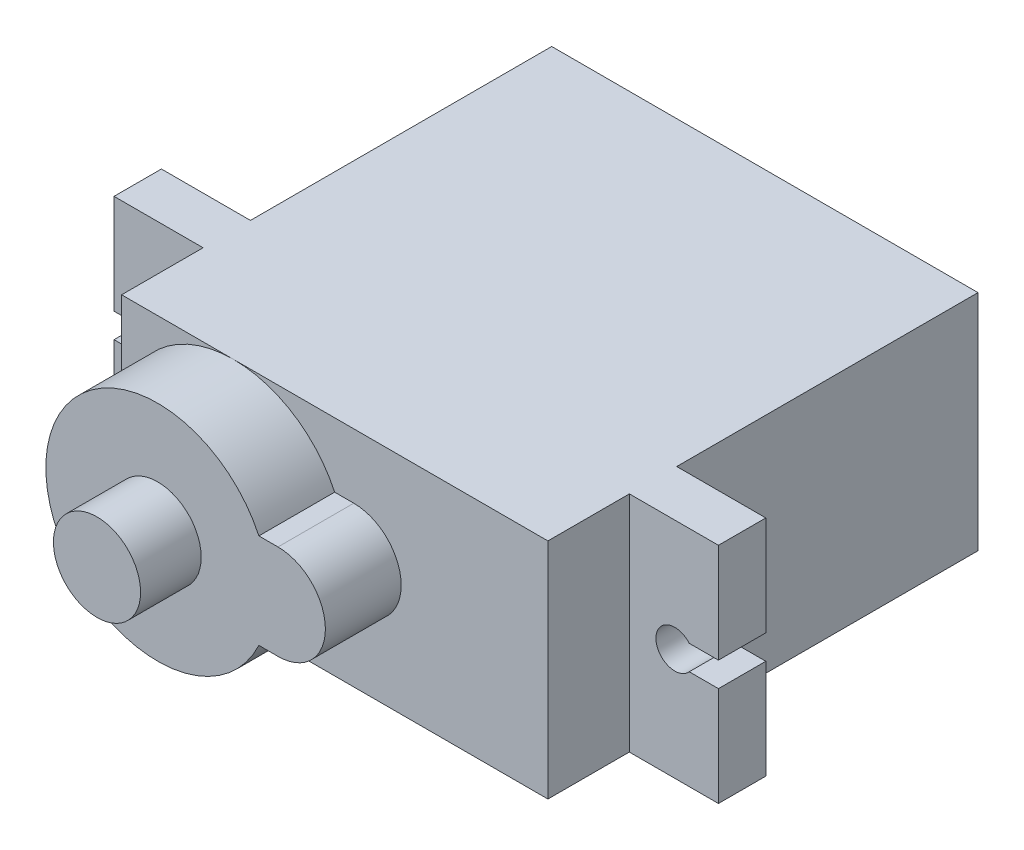
SolidWorks part; units mm, degrees
ref_plane "Alzado" through (0, 0, 0) normal (0, 0, 1) x (1, 0, 0)
ref_plane "Planta" through (0, 0, 0) normal (0, 1, 0) x (1, 0, 0)
ref_plane "Vista lateral" through (0, 0, 0) normal (1, 0, 0) x (0, 0, -1)
sketch "Croquis1" plane through (0, 0, 0) normal (0, 0, 1) x (1, 0, 0)
  line L1 (-11.25, -5.9) -> (11.25, -5.9)
  line L2 (-11.25, -5.9) -> (-11.25, 5.9)
  line L3 (-11.25, 5.9) -> (11.25, 5.9)
  line L4 (11.25, -5.9) -> (11.25, 5.9)
  line L5 (-11.25, -5.9) -> (11.25, 5.9) construction
  line L6 (-11.25, 5.9) -> (11.25, -5.9) construction
  point P0 (0, 0)
  dimension "D1" = 22.5
  dimension "D2" = 11.8
extrude "Saliente-Extruir1" add sketch "Croquis1" along normal blind 22.7
ref_plane "Soportes" through (0, 0, 15.9) normal (0, 0, 1) x (1, 0, 0)
sketch "Croquis2" plane through (0, 0, 15.9) normal (0, 0, 1) x (1, 0, 0)
  line L0 (-13.65, 0) -> (-15.95, -0.002) construction
  line L1 (11.25, 5.9) -> (15.95, 5.9)
  line L2 (11.25, 5.9) -> (11.25, -5.904)
  line L3 (11.25, -5.904) -> (15.95, -5.904)
  line L4 (15.95, 5.9) -> (15.95, 0.648)
  line L5 (-11.25, 5.9) -> (-15.95, 5.9)
  line L6 (-11.25, 5.9) -> (-11.25, -5.904)
  line L7 (-11.25, -5.904) -> (-15.95, -5.904)
  line L8 (-15.95, 5.9) -> (-15.95, 0.648)
  line L10 (-15.95, 0.648) -> (-14.4117, 0.648)
  line L11 (-15.95, -0.652) -> (-14.4082, -0.652)
  line L12 (-15.95, -0.652) -> (-15.95, -5.904)
  line L13 (15.95, 0.648) -> (14.4117, 0.648)
  line L14 (15.95, -0.652) -> (14.4082, -0.652)
  line L15 (15.95, -0.652) -> (15.95, -5.904)
  arc A0 (-14.4082, -0.652) -> (-14.4117, 0.648) centre (-13.65, 0) ccw
  arc A1 (14.4117, 0.648) -> (14.4082, -0.652) centre (13.65, 0) ccw
  point P17 (-15.95, 0.323)
  point P22 (15.95, -0.002)
  dimension "D2" = 5.9
  dimension "D4" = 2.3
  dimension "D6" = 2
  dimension "D1" = 4.7
  dimension "D3" = 2.3
  dimension "D5" = 5.9
  dimension "D7" = 1.3
  dimension "D8" = 1.3
extrude "Saliente-Extruir2" add sketch "Croquis2" along normal blind 2.5
sketch "Croquis3" plane through (0, 0, 22.7) normal (0, 0, 1) x (1, 0, 0)
  line L0 (-11.25, 5.9) -> (-11.25, -5.9) construction
  line L1 (11.25, 0) -> (3.45, 0) construction
  line L2 (11.25, -5.9) -> (11.25, 5.9) construction
  line L4 (1.0032, -2.5023) -> (-0.0069, -2.5023)
  line L5 (1.0032, 2.5001) -> (-0.0059, 2.5001)
  arc A0 (-0.0059, 2.5001) -> (-0.0069, -2.5023) centre (-5.35, 0) ccw
  arc A1 (1.0032, -2.5023) -> (1.0032, 2.5001) centre (1.0032, -0.0011) ccw
  dimension "D1" = 11.8
  dimension "D2" = 5.9
extrude "Saliente-Extruir3" add sketch "Croquis3" along normal blind 4
sketch "Croquis4" plane through (0, 0, 26.7) normal (0, 0, 1) x (1, 0, 0)
  circle A0 centre (-5.35, 0) radius 2.3
  dimension "D1" = 4.6
extrude "Saliente-Extruir4" add sketch "Croquis4" along normal blind 3.2
sketch "Croquis5" plane through (-11.25, 0, 0) normal (-1, 0, 0) x (0, 0, 1)
  line L0 (0, 5.9) -> (0, -5.9) construction
  line L1 (4.5, 1.1) -> (6.3441, 1.1)
  line L2 (4.5, 1.1) -> (4.5, -2.5)
  line L3 (4.5, -2.5) -> (6.3441, -2.5)
  line L4 (6.3441, 1.1) -> (6.3441, -2.5)
  line L7 (0, 0) -> (4.5, -0.7) construction
  line L8 (15.9, 5.9) -> (0, 5.9) construction
  line L10 (15.9, -5.9) -> (0, -5.9) construction
  point P8 (5.4221, 1.1)
  dimension "D1" = 4.5
  dimension "D2" = 4.8
  dimension "D3" = 3.6
  dimension "D4" = 3.4
extrude "Cortar-Extruir1" cut sketch "Croquis5" against normal mid plane 3.2
